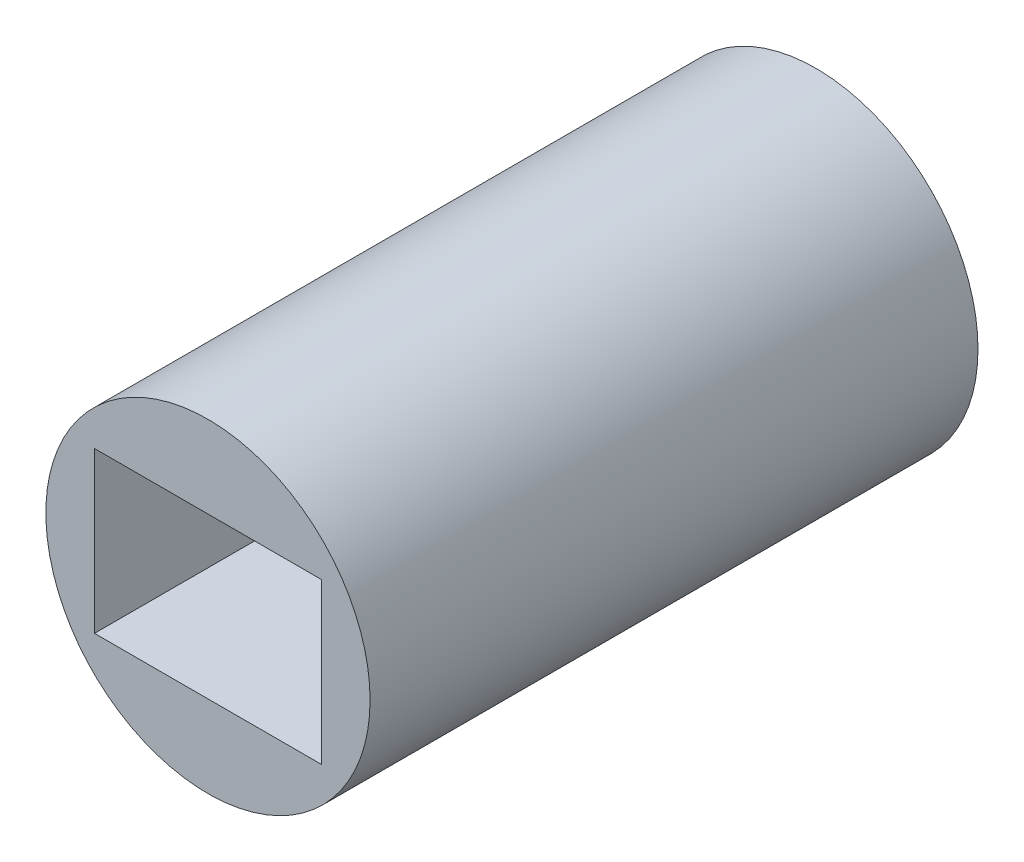
SolidWorks part; units mm, degrees
ref_plane "Front Plane" through (0, 0, 0) normal (0, 0, 1) x (1, 0, 0)
ref_plane "Top Plane" through (0, 0, 0) normal (0, 1, 0) x (1, 0, 0)
ref_plane "Right Plane" through (0, 0, 0) normal (1, 0, 0) x (0, 0, -1)
sketch "Sketch1" plane through (0, 0, 0) normal (0, 0, 1) x (1, 0, 0)
  circle A0 centre (0, 0) radius 4
  dimension "D1" = 8
extrude "Boss-Extrude1" add sketch "Sketch1" along normal blind 15
sketch "Sketch2" plane through (0, 0, 15) normal (0, 0, 1) x (1, 0, 0)
  line L0 (0, 4) -> (0, -4.3128) construction
  line L1 (0, -4.3128) -> (0, 0) construction
  line L2 (0, 0) -> (4.3337, 0) construction
  line L3 (4.3337, 0) -> (-5.3718, 0) construction
  line L5 (-2.8, -1.975) -> (2.8, -1.975)
  line L6 (-2.8, -1.975) -> (-2.8, 1.975)
  line L7 (-2.8, 1.975) -> (2.8, 1.975)
  line L8 (2.8, -1.975) -> (2.8, 1.975)
  line L9 (-2.8, -1.975) -> (2.8, 1.975) construction
  line L10 (-2.8, 1.975) -> (2.8, -1.975) construction
  circle A0 centre (0, 0) radius 4 construction
  dimension "D1" = 3.95
  dimension "D2" = 5.6
extrude "Cut-Extrude1" cut sketch "Sketch2" against normal blind 8
sketch "Sketch3" plane through (0, 0, 0) normal (0, 0, -1) x (-1, 0, 0)
  line L0 (0, -4) -> (0, 4) construction
  line L1 (0, 4) -> (0, 0) construction
  line L2 (0, 0) -> (4, 0) construction
  line L3 (4, 0) -> (-4, 0) construction
  line L6 (-0.0242, -2.4511) -> (0.948, -2.4511) construction
  line L7 (0.948, -2.4511) -> (-0.0242, -2.4511) construction
  line L8 (-0.0242, -2.4511) -> (-0.952, -2.4511) construction
  line L9 (0, 2.4489) -> (0.9458, 2.4489) construction
  line L10 (0.9458, 2.4489) -> (0, 2.4489) construction
  line L11 (0, 2.4489) -> (-0.9542, 2.4489) construction
  line L12 (-2.4531, 0) -> (-2.4531, -0.8145) construction
  line L13 (-2.4531, -0.8145) -> (-2.4531, 0) construction
  line L14 (-2.4531, 0) -> (-2.4531, 0.9477) construction
  line L15 (2.4469, 0) -> (2.4469, 0.95) construction
  line L16 (2.4469, 0) -> (2.4469, -0.95) construction
  line L17 (-2.5675, -0.0023) -> (-2.5675, 0.9477) construction
  line L18 (-2.5675, 0.9477) -> (-0.9726, 0.9477) construction
  line L19 (-0.9726, 0.9477) -> (-0.9726, 2.5477) construction
  line L20 (0.95, 2.5653) -> (0.95, 0.9704) construction
  line L21 (0.95, 0.9704) -> (2.55, 0.9704) construction
  line L22 (2.5675, -0.9523) -> (0.9726, -0.9523) construction
  line L23 (0.9726, -0.9523) -> (0.9726, -2.5523) construction
  line L24 (-0.95, -2.5698) -> (-0.95, -0.9749) construction
  line L25 (-0.95, -0.9749) -> (-2.55, -0.9749) construction
  line L26 (-2.4531, 0.9477) -> (-1.4542, 0.9477)
  line L27 (0.9458, 2.4489) -> (0.9458, 1.45)
  line L28 (2.4469, -0.95) -> (1.448, -0.95)
  line L29 (-0.952, -2.4511) -> (-0.952, -1.4523)
  line L30 (-0.9542, 2.4489) -> (-0.9542, 1.4477)
  line L31 (2.4469, 0.95) -> (1.4458, 0.95)
  line L32 (0.948, -2.4511) -> (0.948, -1.45)
  line L33 (-2.4531, -0.9523) -> (-1.452, -0.9523)
  arc A0 (-0.952, -2.4511) -> (0.948, -2.4511) centre (-0.002, 1.4344) ccw
  circle A1 centre (0, 0) radius 4 construction
  arc A2 (-2.4531, 0.9477) -> (-2.4531, -0.9523) centre (1.4325, -0.0023) ccw
  arc A3 (0.9458, 2.4489) -> (-0.9542, 2.4489) centre (-0.0042, -1.4367) ccw
  arc A4 (2.4469, -0.95) -> (2.4469, 0.95) centre (-1.4386, 0) ccw
  arc A5 (-1.4542, 0.9477) -> (-0.9542, 1.4477) centre (-1.7117, 1.7052) ccw
  arc A6 (0.9458, 1.45) -> (1.4458, 0.95) centre (1.7032, 1.7074) ccw
  arc A7 (0.948, -1.45) -> (1.448, -0.95) centre (1.7645, -1.7664) cw
  arc A8 (-1.452, -0.9523) -> (-0.952, -1.4523) centre (-1.7094, -1.7097) cw
  point P14 (0, 0)
  point P15 (0, 0)
  point P36 (-0.0031, -0.0011)
  point P46 (0, -0.0023)
  point P54 (-0.0031, -0.0011)
  point P61 (-0.0031, -0.0011)
  point P71 (-0.0031, -0.0011)
  dimension "D4" = 4
  dimension "D10" = 4
  dimension "D1" = 4.9
  dimension "D2" = 0.95
  dimension "D3" = 0.95
  dimension "D5" = 4
  dimension "D6" = 4
  dimension "D7" = 4
extrude "Cut-Extrude2" cut sketch "Sketch3" against normal blind 7 contours L32 A7 L28 A4 L31 A6 L27 A3 L30 A5 L26 A2 L33 A8 L29 A0
